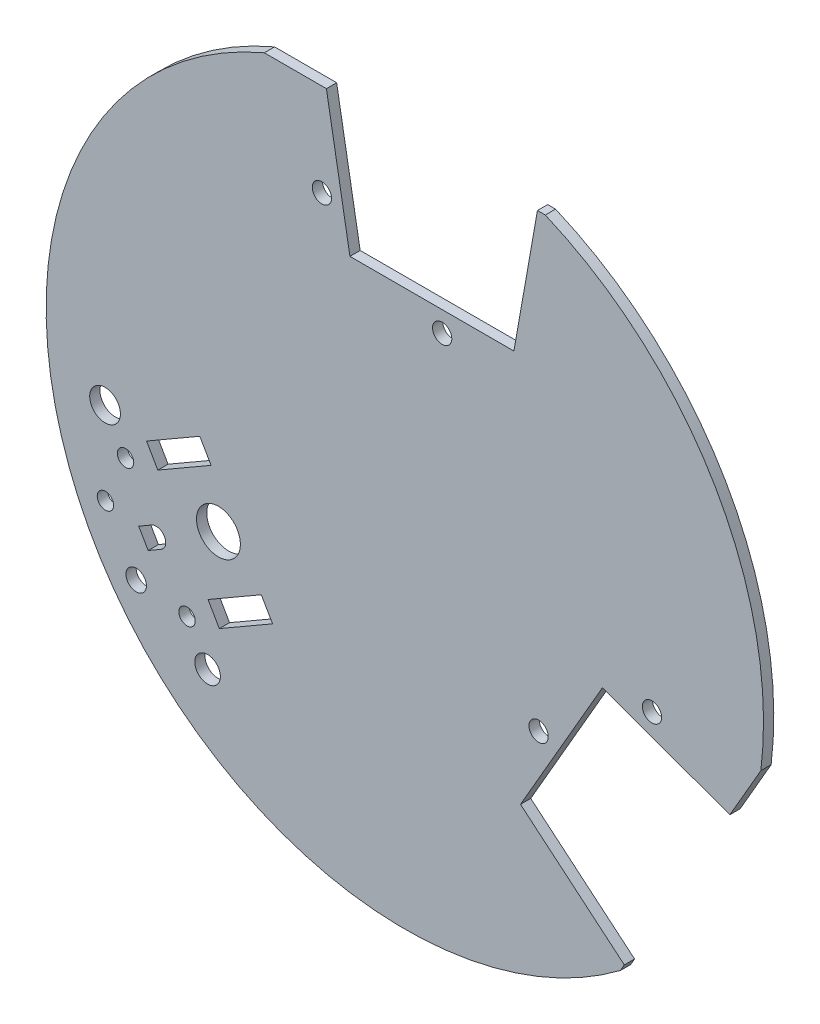
SolidWorks part; units mm, degrees
material "Balsa"
ref_plane "Plan de face" through (0, 0, 0) normal (0, 0, 1) x (1, 0, 0)
ref_plane "Plan de dessus" through (0, 0, 0) normal (0, 1, 0) x (1, 0, 0)
ref_plane "Plan de droite" through (0, 0, 0) normal (1, 0, 0) x (0, 0, -1)
sketch "Esquisse1" plane through (0, 0, 0) normal (0, 0, 1) x (1, 0, 0)
  circle A0 centre (0, 0) radius 175
extrude "Boss.-Extru.1" add sketch "Esquisse1" along normal blind 5
sketch "Esquisse2" plane through (0, 0, 0) normal (0, 0, -1) x (-1, 0, 0)
  line L1 (-13.2204, 90.8876) -> (-13.2204, 0) construction
  line L3 (0, 0) -> (-290.6498, 0) construction
  line L5 (26.7796, 95.8876) -> (38.2633, 161.0152)
  line L6 (38.2633, 161.0152) -> (68.5501, 161.0152)
  line L7 (68.5501, 161.0152) -> (68.5501, 190.2461)
  line L8 (-53.2204, 95.8876) -> (-64.7042, 161.0152)
  line L9 (-64.7042, 161.0152) -> (-94.991, 161.0152)
  line L10 (-94.991, 161.0152) -> (-94.991, 190.2461)
  line L11 (-94.991, 190.2461) -> (68.5501, 190.2461)
  line L12 (26.7796, 95.8876) -> (-53.2204, 95.8876)
  line L13 (-96.4309, -24.752) -> (-158.5749, -47.3706)
  line L14 (-158.5749, -47.3706) -> (-173.7183, -21.1414)
  line L15 (-173.7183, -21.1414) -> (-199.033, -35.7569)
  line L16 (-56.4309, -94.034) -> (-107.0911, -136.543)
  line L17 (-107.0911, -136.543) -> (-91.9477, -162.7722)
  line L18 (-91.9477, -162.7722) -> (-117.2625, -177.3877)
  line L19 (-117.2625, -177.3877) -> (-199.033, -35.7569)
  line L20 (-96.4309, -24.752) -> (-56.4309, -94.034)
  line L21 (-72.1008, -56.893) -> (6.6102, -11.4492) construction
  line L22 (0, 0) -> (87.5, -151.5544) construction
  circle A0 centre (-18.2204, 85.8876) radius 4.7
  circle A1 centre (40.4604, 115.8876) radius 4.7
  circle A2 centre (-65.2706, -58.7232) radius 4.7
  circle A3 centre (-120.5918, -22.9041) radius 4.7
  circle A4 centre (0, 0) radius 175 construction
  point P43 (0, 0)
  dimension "D5" = 9.4
  dimension "D6" = 9.4
  dimension "D1" = 2
  dimension "D2" = 95.8876
  dimension "D3" = 13.2204
  dimension "D4" = 100
  dimension "D7" = 80
  dimension "D8" = 65.1275
extrude "Enlèv. mat.-Extru.1" cut sketch "Esquisse2" against normal blind 5
sketch "Leds, bout., tirette" plane through (0, 0, 5) normal (0, 0, 1) x (1, 0, 0)
  line L0 (0, 0) -> (0, 203.1142) construction
  line L1 (0, 0) -> (-185.8748, -107.3149) construction
  line L2 (-174.6931, -10.359) -> (-97.9423, -10.359) construction
  line L3 (-97.9423, -10.359) -> (-57.9423, -79.641) construction
  line L4 (-57.9423, -79.641) -> (-96.3177, -146.1092) construction
  line L5 (-121.2436, -70) -> (-77.4756, -44.7306) construction
  line L6 (-118.9436, -73.9837) -> (-125.2222, -77.6087)
  line L7 (-123.5436, -66.0163) -> (-129.8222, -69.6413)
  line L8 (-129.8222, -69.6413) -> (-125.2222, -77.6087)
  line L9 (-126.0032, -31.7561) -> (-100.0224, -16.7561)
  line L10 (-126.0032, -31.7561) -> (-120.5032, -41.2824)
  line L11 (-100.0224, -16.7561) -> (-94.5224, -26.2824)
  line L12 (-120.5032, -41.2824) -> (-94.5224, -26.2824)
  line L13 (-96.0032, -83.7176) -> (-70.0224, -68.7176)
  line L14 (-96.0032, -83.7176) -> (-90.5032, -93.2439)
  line L15 (-70.0224, -68.7176) -> (-64.5224, -78.2439)
  line L16 (-90.5032, -93.2439) -> (-64.5224, -78.2439)
  line L17 (-67.2724, -73.4808) -> (-106.2436, -95.9808) construction
  line L18 (-97.2724, -21.5192) -> (-136.2436, -44.0192) construction
  line L19 (-123.5436, -66.0163) -> (-118.9436, -73.9837) construction
  arc A0 (-68.5501, 161.0152) -> (105.1682, -139.8737) centre (0, 0) ccw construction
  arc A1 (-174.6931, -10.359) -> (-96.3177, -146.1092) centre (0, 0) ccw construction
  circle A2 centre (-90.9327, -52.5) radius 10.7
  circle A3 centre (-96.2436, -113.3013) radius 6.25
  circle A4 centre (-136.2436, -44.0192) radius 4
  circle A5 centre (-106.2436, -95.9808) radius 4
  circle A6 centre (-146.0641, -67.0096) radius 4
  circle A7 centre (-131.0641, -92.9904) radius 5
  arc A8 (-118.9436, -73.9837) -> (-123.5436, -66.0163) centre (-121.2436, -70) ccw
  circle A9 centre (-146.2436, -26.6987) radius 7.5
  point P26 (-13.0506, -157.1537)
  dimension "D2" = 90
  dimension "D5" = 12.5
  dimension "D6" = 21.4
  dimension "D7" = 8
  dimension "D8" = 10
  dimension "D9" = 4.6
  dimension "D12" = 15
  dimension "D1" = 120
  dimension "D3" = 80
  dimension "D4" = 120
  dimension "D10" = 9.2
  dimension "D11" = 7.25
  dimension "D13" = 11
  dimension "D14" = 30
  dimension "D15" = 5
  dimension "D16" = 30
  dimension "D17" = 45
  dimension "D18" = 15
  dimension "D19" = 35
  dimension "D20" = 70
  dimension "D21" = 15
  dimension "D22" = 50
  dimension "D23" = 50
extrude "Enlèv. mat.-Extru.2" cut sketch "Leds, bout., tirette" against normal blind 10
